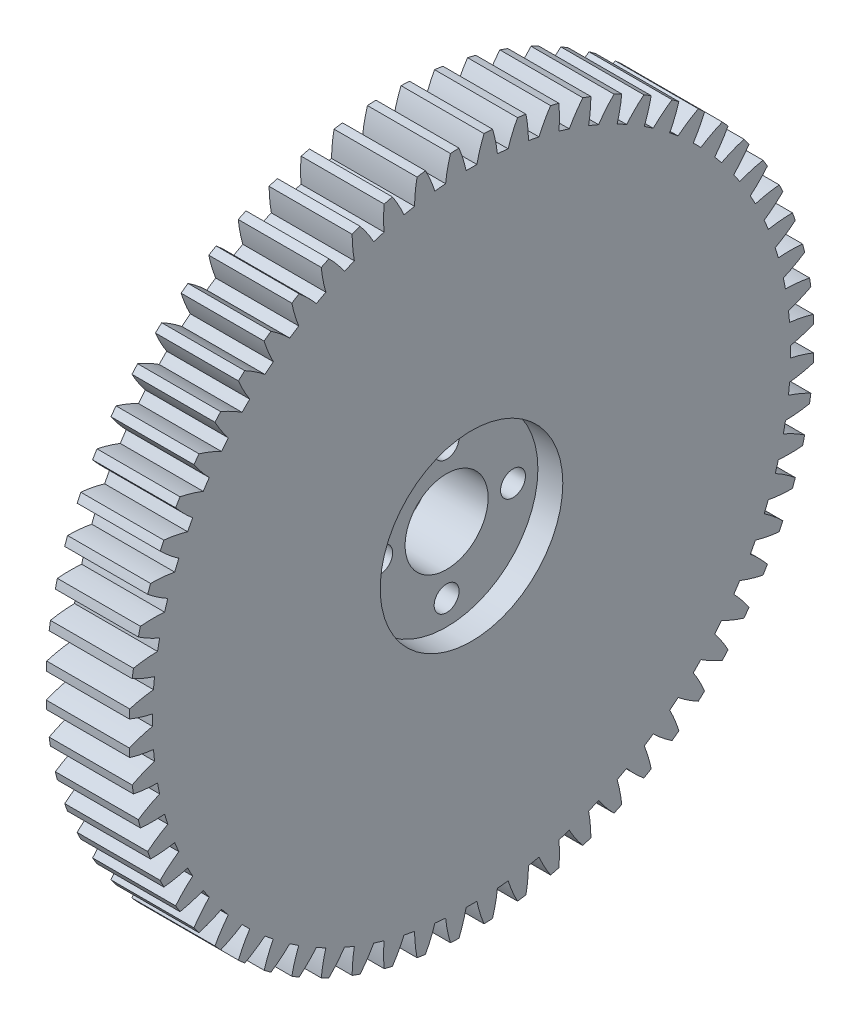
SolidWorks part; units mm, degrees
ref_plane "Plane1" through (0, 0, 0) normal (0, 0, 1) x (1, 0, 0)
ref_plane "Plane2" through (0, 0, 0) normal (0, 1, 0) x (1, 0, 0)
ref_plane "Plane3" through (0, 0, 0) normal (1, 0, 0) x (0, 0, -1)
sketch "HoldingSke" plane through (0, 0, 0) normal (0, 1, 0) x (1, 0, 0)
  line L0 (0, 0) -> (0.3507, -0.719)
  line L1 (-15, 0) -> (100, 0) construction
  line L2 (0, 0) -> (-2.1039, 2.3779)
  line L3 (0, 0) -> (-11.863, 4.5341)
  line L4 (0, 0) -> (3.7858, 7.762)
  line L5 (0, 0) -> (-46.8476, -17.4728)
  line L6 (0, 0) -> (-8.2896, -5.593)
  line L7 (-2.1039, 2.3779) -> (8.6586, 51.2059)
  line L8 (-76.2, 54.61) -> (-75.2, 54.61)
  line L9 (-67.7845, 28.3722) -> (-49.3413, 33.142)
  line L10 (-76.2, 71.12) -> (104.1128, 71.12)
  line L11 (0, 0) -> (-10, 0)
  line L12 (-76.2, 101.6) -> (-76.155, 101.6)
  line L13 (24.9733, 27.94) -> (52.9518, 28.4284)
  line L14 (24.9733, 27.94) -> (24.9743, 27.94)
  line L15 (24.9733, 27.94) -> (100.4006, 29.5858)
  line L16 (-63.627, -1.25) -> (-12.827, -1.25)
  circle A0 centre (0, 0) radius 3
  circle A1 centre (0, 0) radius 37.5
  circle A2 centre (0, 0) radius 37.5
  circle A3 centre (0, 0) radius 3
  dimension "MHD" = 75
  dimension "Hub_dia" = 75
  dimension "Bore" = 6
  dimension "MBD" = 6
  dimension "Num_teeth" = 64
  dimension "Pitch" = 0.8
  dimension "Overall_len" = 50
  dimension "Show_teeth" = 64
  dimension "Thickness" = 10
  dimension "OAL" = 50.0001
  dimension "T_dim" = 1
  dimension "Ap" = 14.5
  dimension "H" = 19.05
  dimension "Pitch_radius" = 180.3128
  dimension "Width" = 10
  dimension "Backlash" = 0.045
  dimension "Addendum_fac" = 1
  dimension "Dedendum_fac" = 1.25
  dimension "Clearance_fac" = 0.25
  dimension "Dedendum_add" = 0.001
  dimension "Module" = 1.25
sketch "BasProSke" plane through (0, 0, 0) normal (0, 1, 0) x (1, 0, 0)
  line L0 (-10, 0) -> (60, 0) construction
  line L1 (0, 0) -> (0, 41.25)
  line L2 (0, 0) -> (10, 0)
  line L3 (10, 0) -> (10, 41.25)
  line L4 (10, 41.25) -> (0, 41.25)
  dimension "Thickness" = 10
  dimension "Diameter" = 82.5
revolve "Base-Revolve" add sketch "BasProSke" angle 360 about L0
sketch "TooCutSke" plane through (0, 0, 0) normal (1, 0, 0) x (0, 0, -1)
  line L1 (0, 0) -> (0, 107) construction
  line L2 (0, 0) -> (-1.0604, 39.9859) construction
  line L3 (0, 0) -> (-3.9244, 79.8833) construction
  line L4 (-1.0604, 39.9859) -> (-1.9622, 39.9416) construction
  arc A0 (0.6495, 38.431) -> (-0.6495, 38.431) centre (0, 0) ccw
  arc A1 (1.5217, 41.2473) -> (-1.5217, 41.2473) centre (0, 0) ccw
  circle A2 centre (0, 0) radius 40 construction
  circle A3 centre (0, 0) radius 38.7259 construction
  arc A4 (-0.6495, 38.431) -> (-1.5217, 41.2473) centre (-16.3045, 35.1263) ccw
  arc A5 (1.5217, 41.2473) -> (0.6495, 38.431) centre (16.3045, 35.1263) ccw
  dimension "Root_dia" = 76.873
  dimension "Overcut_dia" = 82.5508
  dimension "Pitch_dia" = 80
  dimension "Base_dia" = 77.4518
  dimension "Flank_rad" = 16
  dimension "Half_ang" = 2.813
  dimension "Half_CT" = 0.9029
extrude "ToothCut" cut sketch "TooCutSke" along normal through all
fillet "Breaks" [suppressed] radius 0.025
fillet "RootFillets" [suppressed] radius 0.3135
pattern_circular "TeethCuts" count 64 every 5.625 about axis through (-10, 0, 0) along (1, 0, 0) of "ToothCut", "RootFillets", "Breaks"
sketch "HubNeaOneSke" plane through (0, 0, 0) normal (-1, 0, 0) x (0, 0, 1)
  circle A0 centre (0, 0) radius 37.5
  dimension "Diameter" = 75
extrude "HubNearOne" [suppressed] add sketch "HubNeaOneSke" along normal blind 40.0001
sketch "HubNeaBotSke" plane through (0, 0, 0) normal (-1, 0, 0) x (0, 0, 1)
  circle A0 centre (0, 0) radius 37.5
  dimension "Diameter" = 75
extrude "HubNearBoth" [suppressed] add sketch "HubNeaBotSke" along normal blind 20
ref_plane "FarPln" through (10, 0, 0) normal (1, 0, 0) x (0, 0, -1)
sketch "HubFarSke" plane through (10, 0, 0) normal (1, 0, 0) x (0, 0, -1)
  circle A0 centre (0, 0) radius 37.5
  dimension "Diameter" = 75
extrude "HubFar" [suppressed] add sketch "HubFarSke" along normal blind 20
sketch "BorSke" plane through (0, 0, 0) normal (1, 0, 0) x (0, 0, -1)
  circle A0 centre (0, 0) radius 3
  dimension "Diameter" = 6
extrude "Bore" cut sketch "BorSke" along normal mid plane 100.0001
sketch "KeySke" plane through (0, 0, 0) normal (1, 0, 0) x (0, 0, -1)
  line L0 (-1, 0) -> (-1, 4)
  line L1 (-1, 4) -> (1, 4)
  line L2 (1, 4) -> (1, 0)
  line L3 (0, 0) -> (0, 34) construction
  line L4 (-1, 0) -> (1, 0)
  dimension "Offset" = 4
  dimension "Width" = 2
extrude "Keyway" [suppressed] cut sketch "KeySke" along normal mid plane 100.0001
pattern_circular "Keyway2" [suppressed] count 2 every 90 about axis through (-10, 0, 0) along (1, 0, 0)
sketch "Sketch1" plane through (10, 0, 0) normal (1, 0, 0) x (0, 0, -1)
  circle A0 centre (0, 0) radius 8 construction
  circle A1 centre (0, 8) radius 1.5
  circle A2 centre (8, 0) radius 1.5
  circle A3 centre (0, -8) radius 1.5
  circle A4 centre (-8, 0) radius 1.5
  point P14 (0, 0)
  dimension "D1" = 16
  dimension "D2" = 3
  dimension "D3" = 4
extrude "Cut-Extrude1" cut sketch "Sketch1" against normal blind 10
sketch "Sketch2" plane through (10, 0, 0) normal (1, 0, 0) x (0, 0, -1)
  circle A0 centre (0, 0) radius 11
  dimension "D1" = 22
extrude "Cut-Extrude2" cut sketch "Sketch2" against normal blind 3
sketch "Sketch3" plane through (7, 0, 0) normal (1, 0, 0) x (0, 0, -1)
  circle A0 centre (0, 0) radius 5
  dimension "D1" = 10
extrude "Cut-Extrude4" cut sketch "Sketch3" against normal up to next
sketch "Sketch4" plane through (0, 0, 0) normal (-1, 0, 0) x (0, 0, 1)
  circle A0 centre (0, 8) radius 2.25
  circle A1 centre (8, 0) radius 2.25
  circle A2 centre (0, -8) radius 2.25
  circle A3 centre (-8, 0) radius 2.25
  point P12 (0, 0)
  dimension "D1" = 4.5
  dimension "D2" = 4
extrude "Cut-Extrude5" cut sketch "Sketch4" against normal blind 2
equation "' \"Module@HoldingSke\" = 6.35"
equation "' \"Num_teeth@HoldingSke\" = 12"
equation "' \"Ap@HoldingSke\" =  20"
equation "' \"Ap@HoldingSke\" = 20"
equation "' \"Width@HoldingSke\" = 0.5 * 25.4"
equation "' \"Hub_dia@HoldingSke\"= 1 * 25.4"
equation "' \"Hub_dia@HoldingSke\" = 1 * 25.4"
equation "' \"Overall_len@HoldingSke\" = 1.0 * 25.4"
equation "' \"Bore@HoldingSke\" = 0.75 * 25.4"
equation "' \"T_dim@HoldingSke\" = 0.1 * 25.4"
equation "' \"Width@KeySke\" = 0.25 * 25.4"
equation "' \"Show_teeth@HoldingSke\" = 13"
equation "' \"Backlash@HoldingSke\" = 0.009 * 25.4"
equation "' \"Addendum_fac@HoldingSke\" = 1.0"
equation "' \"Dedendum_fac@HoldingSke\" = 1.25"
equation "' \"Dedendum_add@HoldingSke\" = 0.00005 * 25.4"
equation "' \"Clearance_fac@HoldingSke\" = 0.25"
equation "\"Pitch@HoldingSke\" = 1 / \"Module@HoldingSke\""
equation "\"Overcut_dia@TooCutSke\" = (\"Num_teeth@HoldingSke\" + 2 * \"Addendum_fac@HoldingSke\") / \"Pitch@HoldingSke\" + 0.002 * 25.4"
equation "\"Pitch_dia@TooCutSke\" = \"Num_teeth@HoldingSke\" / \"Pitch@HoldingSke\""
equation "\"Base_dia@TooCutSke\" = \"Num_teeth@HoldingSke\" / \"Pitch@HoldingSke\" * cos((\"Ap@HoldingSke\"  * 3.14159265 / 180))"
equation "\"Root_dia@TooCutSke\" = (\"Num_teeth@HoldingSke\" + 2) / \"Pitch@HoldingSke\" - 2 * (\"Addendum_fac@HoldingSke\" + \"Dedendum_fac@HoldingSke\") / \"Pitch@HoldingSke\" - \"Dedendum_add@HoldingSke\" * 2"
equation "\"Half_ang@TooCutSke\" = 180 / \"Num_teeth@HoldingSke\""
equation "\"Half_CT@TooCutSke\" = \"Num_teeth@HoldingSke\" / \"Pitch@HoldingSke\" * sin((3.14159265 / 2 / \"Num_teeth@HoldingSke\")) / 2 - 7 * \"Backlash@HoldingSke\" / 4"
equation "\"Flank_rad@TooCutSke\" = \"Num_teeth@HoldingSke\" / \"Pitch@HoldingSke\" / 5"
equation "\"Radius@RootFillets\" = \"Clearance_fac@HoldingSke\" / \"Pitch@HoldingSke\" + \"Dedendum_add@HoldingSke\""
equation "\"Break_rad@Breaks\" = 0.02 / \"Pitch@HoldingSke\""
equation "\"Thickness@HoldingSke\" = \"Width@HoldingSke\""
equation "\"OAL@HoldingSke\" = \"Thickness@HoldingSke\""
equation "\"MHD@HoldingSke\" = (\"Num_teeth@HoldingSke\" + 2) / \"Pitch@HoldingSke\" - 2 * (\"Addendum_fac@HoldingSke\" + \"Dedendum_fac@HoldingSke\")  / \"Pitch@HoldingSke\" - \"Dedendum_add@HoldingSke\" * 2"
equation "\"MBD@HoldingSke\" = (\"Num_teeth@HoldingSke\" + 2) / \"Pitch@HoldingSke\" - 2 * (\"Addendum_fac@HoldingSke\" + \"Dedendum_fac@HoldingSke\")  / \"Pitch@HoldingSke\" - \"Dedendum_add@HoldingSke\" * 2 - 0.002 * 25.4"
equation "\"MHD@HoldingSke\" = ((sgn( \"MHD@HoldingSke\" - \"Hub_dia@HoldingSke\" )-1)*( \"MHD@HoldingSke\" - \"Hub_dia@HoldingSke\" ))/-2+ \"Hub_dia@HoldingSke\""
equation "\"MBD@HoldingSke\" = ((sgn( \"MBD@HoldingSke\" - \"Bore@HoldingSke\" )-1)*( \"MBD@HoldingSke\" - \"Bore@HoldingSke\" ))/-2+ \"Bore@HoldingSke\""
equation "\"OAL@HoldingSke\" = ((sgn( \"OAL@HoldingSke\" - \"Overall_len@HoldingSke\" )+1)*( \"OAL@HoldingSke\" - \"Overall_len@HoldingSke\" ))/2 + \"Overall_len@HoldingSke\" + 0.000002 * 25.4"
equation "\"Num_teeth@TeethCuts\" = int( \"Show_teeth@HoldingSke\" ) + 1"
equation "\"Num_teeth@TeethCuts\" = ((sgn( \"Num_teeth@TeethCuts\" - \"Num_teeth@HoldingSke\" )-1)*( \"Num_teeth@TeethCuts\" - \"Num_teeth@HoldingSke\" ))/-2+ \"Num_teeth@HoldingSke\""
equation "\"Num_teeth@TeethCuts\" = ((sgn( \"Num_teeth@TeethCuts\" - 2.0)+1)*( \"Num_teeth@TeethCuts\" - 2.0))/2 +2.0"
equation "\"Angle@TeethCuts\" = 360.0 / \"Num_teeth@HoldingSke\""
equation "\"Diameter@BasProSke\" = (\"Num_teeth@HoldingSke\" + 2 * \"Addendum_fac@HoldingSke\") / \"Pitch@HoldingSke\""
equation "\"Thickness@BasProSke\"  = \"Thickness@HoldingSke\""
equation "' \"Fillet_rad@BasProSke\" =  \"Thickness@HoldingSke\" * 0.05"
equation "' \"Fillet_rad@BasProSke\" = \"Thickness@HoldingSke\" * 0.05"
equation "\"MHD@HoldingSke\" = ((sgn( \"MHD@HoldingSke\" - \"Root_dia@TooCutSke\" )-1)*( \"MHD@HoldingSke\" - \"Root_dia@TooCutSke\" ))/-2+ \"Root_dia@TooCutSke\""
equation "\"Diameter@HubNeaOneSke\" = \"MHD@HoldingSke\""
equation "\"Length@HubNearOne\" = \"OAL@HoldingSke\" - \"Thickness@BasProSke\""
equation "\"Diameter@HubNeaBotSke\" = \"MHD@HoldingSke\""
equation "\"Length@HubNearBoth\" = ( \"OAL@HoldingSke\" - \"Thickness@BasProSke\" ) / 2.0"
equation "\"Thickness@FarPln\" = \"Thickness@BasProSke\""
equation "\"Diameter@HubFarSke\" = \"MHD@HoldingSke\""
equation "\"Length@HubFar\" = ( \"OAL@HoldingSke\" - \"Thickness@BasProSke\" ) / 2.0"
equation "\"Diameter@BorSke\" = \"MBD@HoldingSke\""
equation "\"D1@Bore\" = \"OAL@HoldingSke\" * 2.0"
equation "\"D1@Keyway\" = \"OAL@HoldingSke\" * 2.0"
equation "\"Offset@KeySke\" = \"T_dim@HoldingSke\" + \"MBD@HoldingSke\" / 2.0"
